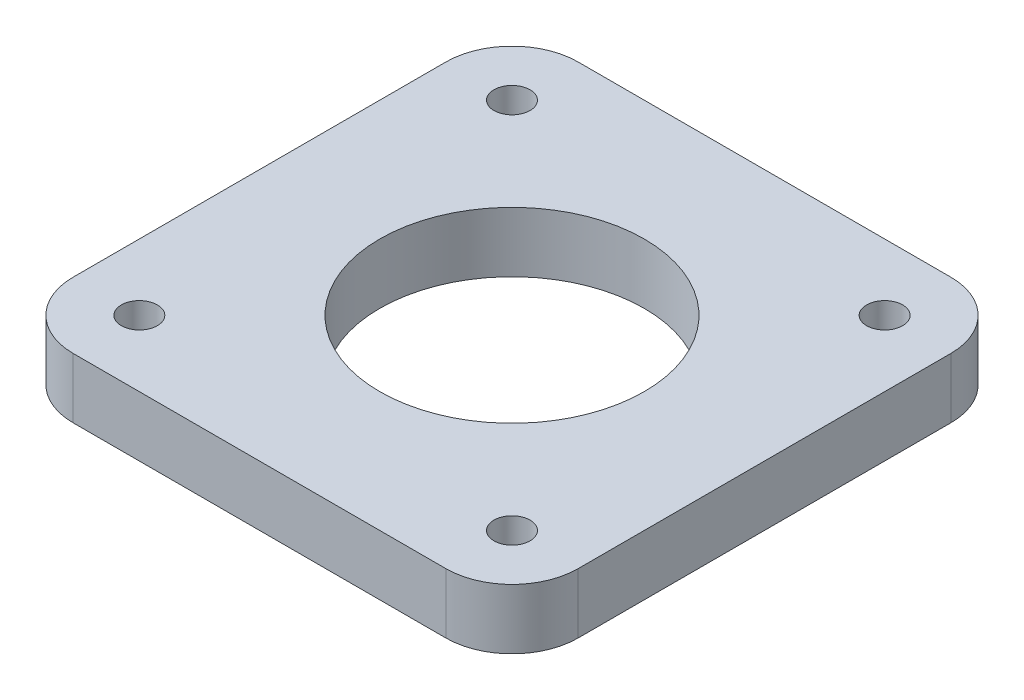
SolidWorks part; units mm, degrees
ref_plane "前基準面" through (0, 0, 0) normal (0, 0, 1) x (1, 0, 0)
ref_plane "上基準面" through (0, 0, 0) normal (0, 1, 0) x (1, 0, 0)
ref_plane "右基準面" through (0, 0, 0) normal (1, 0, 0) x (0, 0, -1)
sketch "草圖1" plane through (0, 0, 0) normal (0, 1, 0) x (1, 0, 0)
  line L1 (-15.5, 12.4526) -> (15.5, 12.4526)
  line L2 (-21, 6.9526) -> (-21, -24.0474)
  line L3 (-15.5, -29.5474) -> (15.5, -29.5474)
  line L4 (21, 6.9526) -> (21, -24.0474)
  circle A0 centre (15.5, 6.9526) radius 1.5
  circle A1 centre (15.5, -24.0474) radius 1.5
  circle A2 centre (-15.5, 6.9526) radius 1.5
  circle A3 centre (-15.5, -24.0474) radius 1.5
  arc A4 (21, -24.0474) -> (15.5, -29.5474) centre (15.5, -24.0474) cw
  arc A5 (15.5, 12.4526) -> (21, 6.9526) centre (15.5, 6.9526) cw
  arc A6 (-15.5, 12.4526) -> (-21, 6.9526) centre (-15.5, 6.9526) ccw
  arc A7 (-21, -24.0474) -> (-15.5, -29.5474) centre (-15.5, -24.0474) ccw
  circle A8 centre (0, -8.5474) radius 11
  dimension "D3" = 3
  dimension "D1" = 22
  dimension "D2" = 42
  dimension "D4" = 5.5
  dimension "D5" = 5.5
  dimension "D6" = 31
  dimension "D7" = 21
  dimension "D8" = 21
extrude "填料-伸長1" add sketch "草圖1" along normal blind 5
